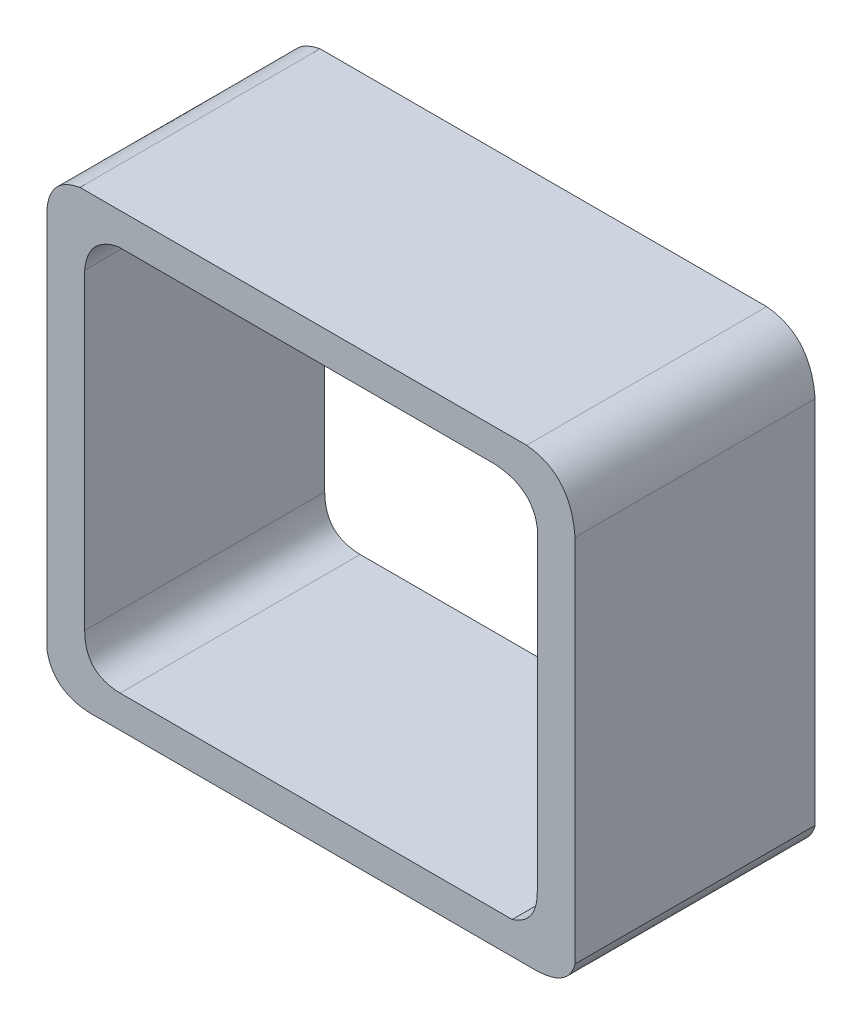
SolidWorks part; units mm, degrees
ref_plane "Front Plane" through (0, 0, 0) normal (0, 0, 1) x (1, 0, 0)
ref_plane "Top Plane" through (0, 0, 0) normal (0, 1, 0) x (1, 0, 0)
ref_plane "Right Plane" through (0, 0, 0) normal (1, 0, 0) x (0, 0, -1)
sketch "Sketch3" plane through (0, 0, 0) normal (0, 0, 1) x (1, 0, 0)
  line L1 (-15.395, 15) -> (14.3721, 15)
  line L2 (-17.6043, 12.4075) -> (-17.6043, -12.7761)
  line L3 (-13.9896, -15) -> (15.0827, -15)
  line L4 (17.6043, 11.3034) -> (17.6043, -13.3241)
  line L7 (-12.8689, 12.8514) -> (12.2904, 12.8514)
  line L8 (-15.0827, 10.375) -> (-15.0827, -10.4228)
  line L9 (-12.7203, -12.8514) -> (13.4155, -12.8514)
  line L10 (15.0827, 10.6131) -> (15.0827, -10.4228)
  spline S0 degree 2 poles (-17.6043, 12.4075) (-17.5421, 14.6102) (-15.395, 15) knots 0 0 0 1 1 1
  spline S1 degree 2 poles (-15.0827, 10.375) (-14.9019, 12.4222) (-12.8689, 12.8514) knots 0 0 0 1 1 1
  spline S2 degree 3 poles (14.3721, 15) (16.3443, 14.8062) (17.4217, 13.5739) (17.6043, 11.3034) knots 0.157317 0.157317 0.157317 0.157317 1 1 1 1
  spline S3 degree 3 poles (12.2904, 12.8514) (13.9377, 12.7166) (14.8685, 11.9705) (15.0827, 10.6131) knots 0 0 0 0 0.769802 0.769802 0.769802 0.769802
  spline S4 degree 2 poles (-15.0827, -10.4228) (-15.0791, -12.7992) (-12.7203, -12.8514) knots 0 0 0 1 1 1
  spline S5 degree 3 poles (-17.6043, -12.7761) (-17.2903, -14.3903) (-16.0853, -15.1316) (-13.9896, -15) knots 0.260635 0.260635 0.260635 0.260635 1 1 1 1
  spline S6 degree 2 poles (15.0827, -10.4228) (15.0812, -12.3166) (13.4155, -12.8514) knots 0 0 0 1 1 1
  spline S7 degree 3 poles (17.6043, -13.3241) (17.3371, -14.3776) (16.4966, -14.9362) (15.0827, -15) knots 0.317898 0.317898 0.317898 0.317898 1 1 1 1
  point P0 (0, 0)
  point P6 (0, 0)
extrude "Boss-Extrude4" add sketch "Sketch3" along normal blind 16
